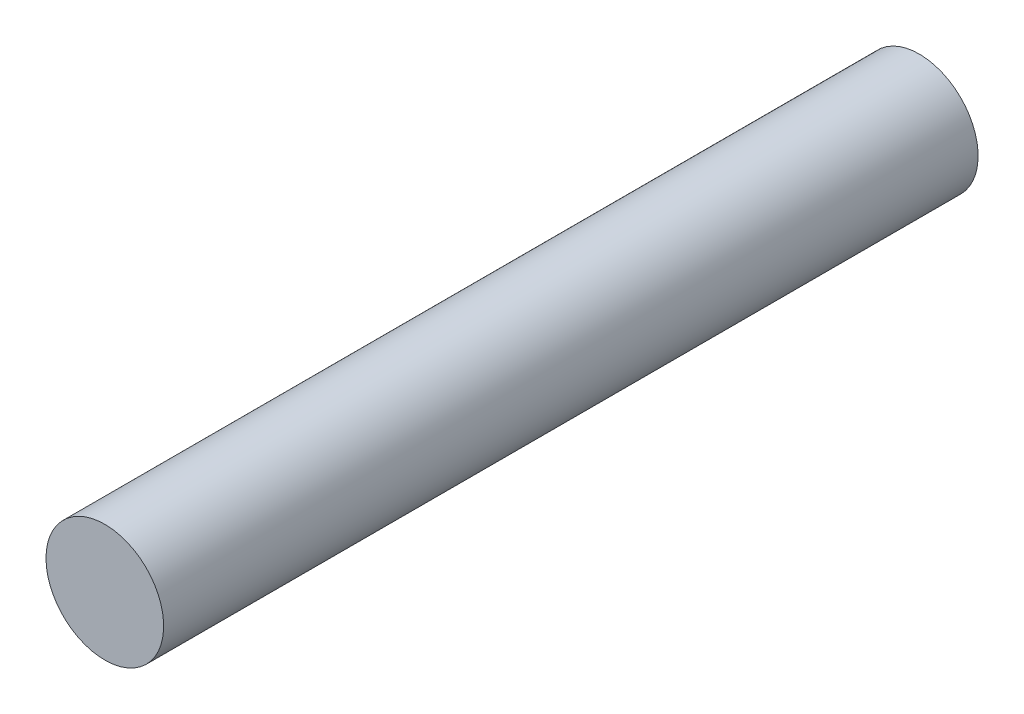
SolidWorks part; units mm, degrees
ref_plane "Спереди" through (0, 0, 0) normal (0, 0, 1) x (1, 0, 0)
ref_plane "Сверху" through (0, 0, 0) normal (0, 1, 0) x (1, 0, 0)
ref_plane "Справа" through (0, 0, 0) normal (1, 0, 0) x (0, 0, -1)
sketch "Эскиз1" plane through (0, 0, 0) normal (0, 0, 1) x (1, 0, 0)
  circle A0 centre (0, 0) radius 6.5
  dimension "D1" = 13
extrude "Бобышка-Вытянуть1" add sketch "Эскиз1" along normal blind 90
